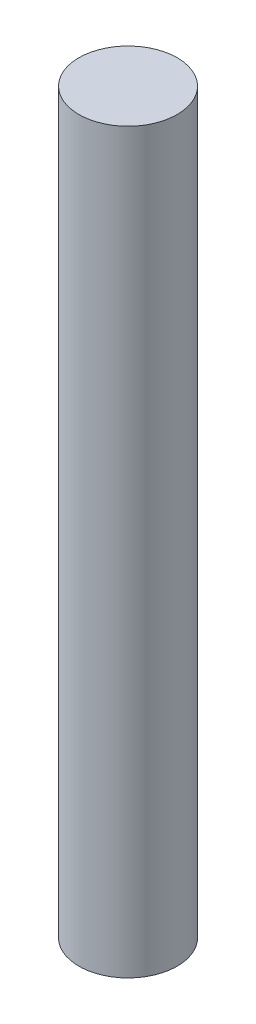
SolidWorks part; units mm, degrees
ref_plane "Front Plane" through (0, 0, 0) normal (0, 0, 1) x (1, 0, 0)
ref_plane "Top Plane" through (0, 0, 0) normal (0, 1, 0) x (1, 0, 0)
ref_plane "Right Plane" through (0, 0, 0) normal (1, 0, 0) x (0, 0, -1)
sketch "Sketch1" plane through (0, 0, 0) normal (0, 1, 0) x (1, 0, 0)
  circle A0 centre (0, 0) radius 5.08
  dimension "D1" = 10.16
extrude "Boss-Extrude1" add sketch "Sketch1" along normal blind 76.2
